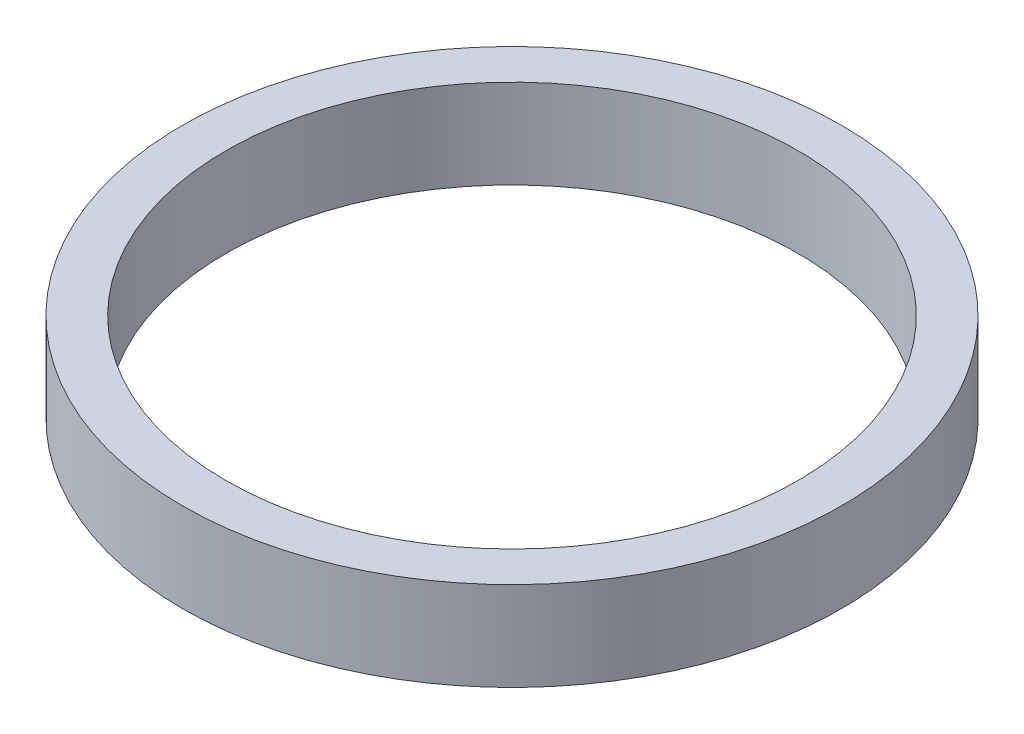
SolidWorks part; units mm, degrees
ref_plane "Front Plane" through (0, 0, 0) normal (0, 0, 1) x (1, 0, 0)
ref_plane "Top Plane" through (0, 0, 0) normal (0, 1, 0) x (1, 0, 0)
ref_plane "Right Plane" through (0, 0, 0) normal (1, 0, 0) x (0, 0, -1)
sketch "Sketch2" plane through (0, 9, 0) normal (0, 1, 0) x (1, 0, 0)
  circle A0 centre (-0.5, 0) radius 18.5 construction
  circle A7 centre (-0.5, 0) radius 18.5
  circle A15 centre (-0.5, 0) radius 16.05
  dimension "D1" = 37
  dimension "D2" = 32.1
extrude "Boss-Extrude1" add sketch "Sketch2" along normal blind 5
